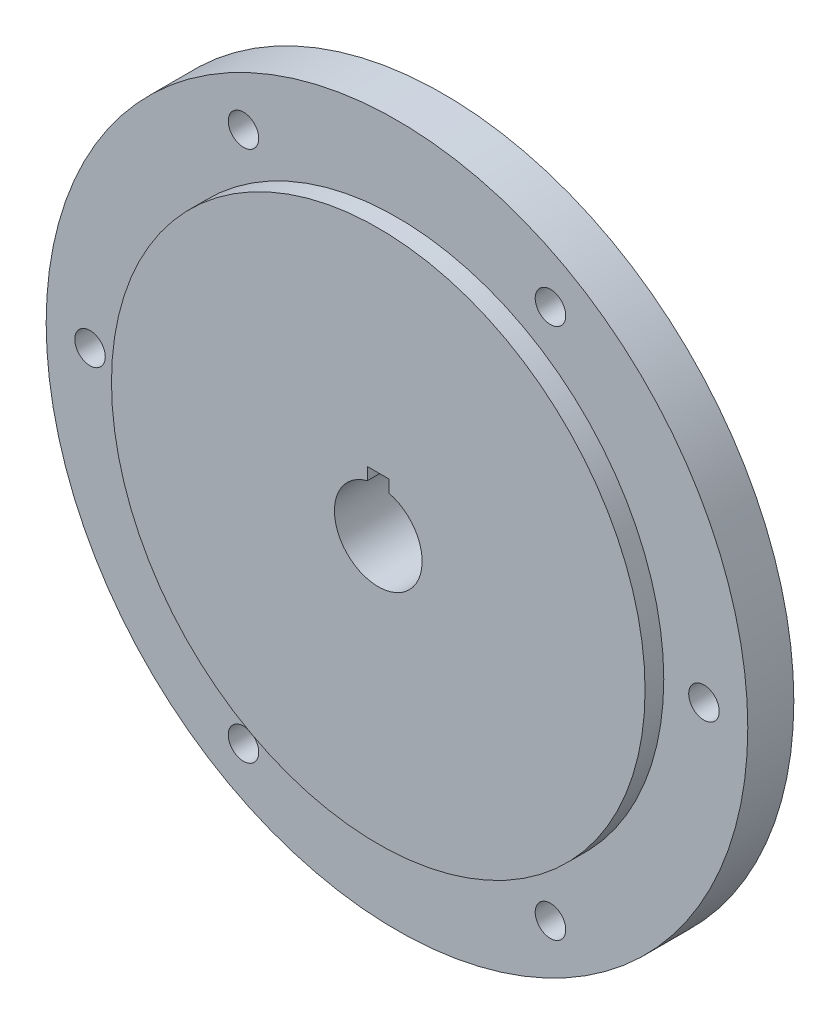
SolidWorks part; units mm, degrees
ref_plane "Front Plane" through (0, 0, 0) normal (0, 0, 1) x (1, 0, 0)
ref_plane "Top Plane" through (0, 0, 0) normal (0, 1, 0) x (1, 0, 0)
ref_plane "Right Plane" through (0, 0, 0) normal (1, 0, 0) x (0, 0, -1)
sketch "Sketch1" plane through (0, 0, 0) normal (0, 0, 1) x (1, 0, 0)
  circle A0 centre (0, 0) radius 76.2
  dimension "D1" = 152.4
extrude "Boss-Extrude1" add sketch "Sketch1" along normal blind 10
sketch "Sketch2" plane through (0, 0, 0) normal (0, 0, 1) x (1, 0, 0)
  line L0 (0, 0) -> (66.675, 0) construction
  line L1 (0, 0) -> (33.3375, -57.7422) construction
  line L2 (0, 0) -> (-33.3375, -57.7422) construction
  line L3 (0, 0) -> (-66.675, 0) construction
  line L4 (0, 0) -> (-33.3375, 57.7422) construction
  line L5 (0, 0) -> (33.3375, 57.7422) construction
  circle A0 centre (66.675, 0) radius 3.3147
  circle A1 centre (33.3375, -57.7422) radius 3.3147
  circle A2 centre (-33.3375, -57.7422) radius 3.3147
  circle A3 centre (-66.675, 0) radius 3.3147
  circle A4 centre (-33.3375, 57.7422) radius 3.3147
  circle A5 centre (33.3375, 57.7422) radius 3.3147
  point P17 (0, 0)
  dimension "D2" = 6.6294
  dimension "D1" = 66.675
  dimension "D3" = 6
extrude "Cut-Extrude2" cut sketch "Sketch2" along direction (0, 0, 1) on the side of the normal through all
sketch "Sketch4" plane through (0, 0, 10) normal (0, 0, 1) x (1, 0, 0)
  circle A0 centre (0, 0) radius 57.9501
extrude "Boss-Extrude2" add sketch "Sketch4" along normal blind 4.064
sketch "Sketch6" plane through (0, 0, 14.064) normal (0, 0, 1) x (1, 0, 0)
  line L0 (0, 0) -> (0, 9.525) construction
  line L1 (-2.3813, 11.9062) -> (2.3813, 11.9062)
  line L2 (-2.3813, 11.9062) -> (-2.3813, 7.1437)
  line L3 (-2.3813, 7.1437) -> (2.3813, 7.1437)
  line L4 (2.3813, 11.9062) -> (2.3813, 7.1437)
  circle A0 centre (0, 0) radius 9.525
  point P7 (2.3813, 9.525)
  point P9 (0, 11.9062)
  point P11 (0, 9.525)
  point P12 (0, 7.1437)
  dimension "D1" = 4.7625
  dimension "D2" = 4.7625
extrude "Cut-Extrude3" cut sketch "Sketch6" against normal through all
